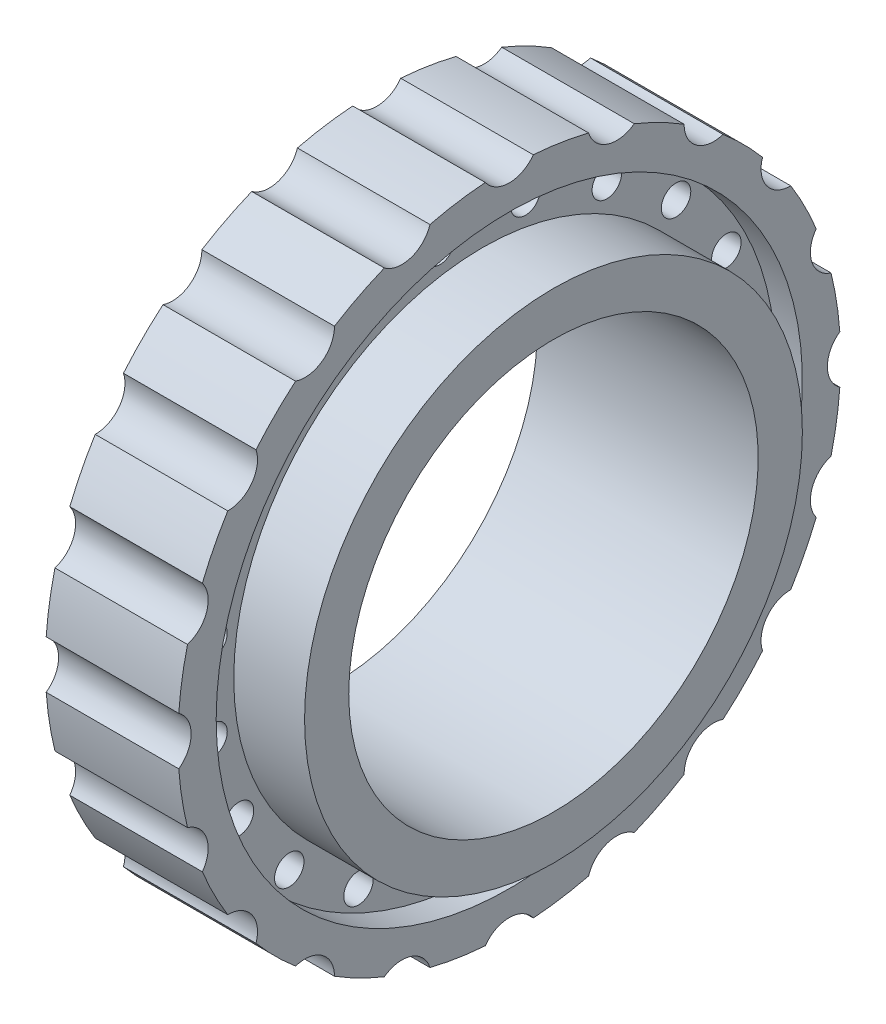
SolidWorks part; units mm, degrees
ref_plane "Front Plane" through (0, 0, 0) normal (0, 0, 1) x (1, 0, 0)
ref_plane "Top Plane" through (0, 0, 0) normal (0, 1, 0) x (1, 0, 0)
ref_plane "Right Plane" through (0, 0, 0) normal (1, 0, 0) x (0, 0, -1)
sketch "Sketch2" plane through (0, 0, 0) normal (0, 0, 1) x (1, 0, 0)
  line L0 (0, 13.9) -> (0, -39.4157) construction
  line L1 (7.5, 13.9) -> (-7.5, 13.9)
  line L2 (-32.7204, 0) -> (0, 0) construction
  line L3 (-7.5, 13.9) -> (-7.5, 16.9)
  line L4 (-7.5, 16.9) -> (-2.6929, 16.9)
  line L5 (-2.6929, 16.9) -> (-2.6929, 19.9)
  line L7 (-32.7204, 32.5) -> (17.6281, 32.5) construction
  line L8 (2.6929, 16.9) -> (2.6929, 19.9)
  line L9 (17.6281, 22.5) -> (-32.7204, 22.5) construction
  line L10 (7.5, 16.9) -> (2.6929, 16.9)
  line L11 (7.5, 13.9) -> (7.5, 16.9)
  line L12 (-2.6929, 19.9) -> (-4.5, 19.9)
  line L13 (-4.5, 19.9) -> (-4.5, 22.5)
  line L14 (-4.5, 22.5) -> (4.5, 22.5)
  line L15 (4.5, 19.9) -> (4.5, 22.5)
  line L16 (2.6929, 19.9) -> (4.5, 19.9)
  point P18 (0, 13.9)
  point P22 (0, 22.5)
  dimension "D1" = 27.8
  dimension "D2" = 15
  dimension "D3" = 32.5
  dimension "D4" = 10
  dimension "D5" = 3
  dimension "D6" = 3
  dimension "D7" = 3
revolve "Revolve1" add sketch "Sketch2" angle 360 about L2
sketch "Sketch3" plane through (0, 0, 0) normal (1, 0, 0) x (0, 0, -1)
  line L0 (-2.9049, 18.341) -> (0, 0) construction
  line L1 (0, 0) -> (0, 23.5996) construction
  circle A0 centre (7.2927, 22.4445) radius 2
  circle A1 centre (-2.9049, 18.341) radius 1
  circle A2 centre (13.8715, 19.0925) radius 2
  circle A3 centre (19.0925, 13.8715) radius 2
  circle A4 centre (22.4445, 7.2927) radius 2
  circle A5 centre (23.5996, 0) radius 2
  circle A6 centre (22.4445, -7.2927) radius 2
  circle A7 centre (19.0925, -13.8715) radius 2
  circle A8 centre (13.8715, -19.0925) radius 2
  circle A9 centre (7.2927, -22.4445) radius 2
  circle A10 centre (0, -23.5996) radius 2
  circle A11 centre (-7.2927, -22.4445) radius 2
  circle A12 centre (-13.8715, -19.0925) radius 2
  circle A13 centre (-19.0925, -13.8715) radius 2
  circle A14 centre (-22.4445, -7.2927) radius 2
  circle A15 centre (-23.5996, 0) radius 2
  circle A16 centre (-22.4445, 7.2927) radius 2
  circle A17 centre (-19.0925, 13.8715) radius 2
  circle A18 centre (-13.8715, 19.0925) radius 2
  circle A19 centre (-7.2927, 22.4445) radius 2
  circle A20 centre (0, 23.5996) radius 2
  circle A21 centre (2.9049, 18.341) radius 1
  circle A22 centre (8.4304, 16.5457) radius 1
  circle A23 centre (13.1307, 13.1307) radius 1
  circle A24 centre (16.5457, 8.4304) radius 1
  circle A25 centre (18.341, 2.9049) radius 1
  circle A26 centre (18.341, -2.9049) radius 1
  circle A27 centre (16.5457, -8.4304) radius 1
  circle A28 centre (13.1307, -13.1307) radius 1
  circle A29 centre (8.4304, -16.5457) radius 1
  circle A30 centre (2.9049, -18.341) radius 1
  circle A31 centre (-2.9049, -18.341) radius 1
  circle A32 centre (-8.4304, -16.5457) radius 1
  circle A33 centre (-13.1307, -13.1307) radius 1
  circle A34 centre (-16.5457, -8.4304) radius 1
  circle A35 centre (-18.341, -2.9049) radius 1
  circle A36 centre (-18.341, 2.9049) radius 1
  circle A37 centre (-16.5457, 8.4304) radius 1
  circle A38 centre (-13.1307, 13.1307) radius 1
  circle A39 centre (-8.4304, 16.5457) radius 1
  point P44 (0, 0)
  point P85 (0, 0)
  dimension "D2" = 4
  dimension "D5" = 2
  dimension "D3" = 9
  dimension "D1" = 20
  dimension "D4" = 20
extrude "Cut-Extrude1" cut sketch "Sketch3" against normal through all both and the other way through all
